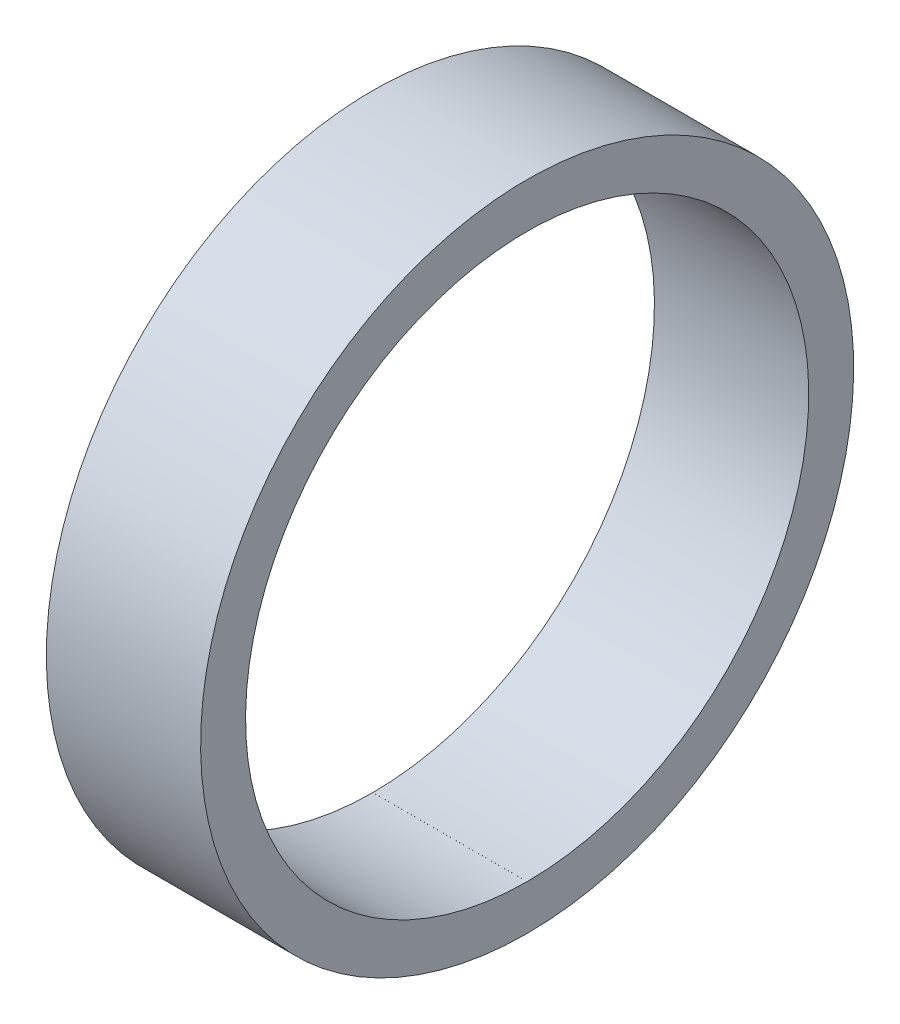
SolidWorks part; units mm, degrees
ref_plane "Front Plane" through (0, 0, 0) normal (0, 0, 1) x (1, 0, 0)
ref_plane "Top Plane" through (0, 0, 0) normal (0, 1, 0) x (1, 0, 0)
ref_plane "Right Plane" through (0, 0, 0) normal (1, 0, 0) x (0, 0, -1)
sketch "Sketch1" plane through (0, 0, 0) normal (0, 0, 1) x (1, 0, 0)
  line L0 (0, 0) -> (26.162, 0)
  line L1 (0, 47.752) -> (26.162, 47.752) construction
  dimension "D1" = 26.162
  dimension "D2" = 47.752
revolve "Revolve-Thin1" add sketch "Sketch1" angle 359.99 about L1
equation "\"FoamCore\" = \".2\""
equation "\"MDF\" = \".2\""
equation "\"GMaterial\"= \".2\""
equation "\"PVCMountDiameter\" = \"0.5in\""
equation "\"PVCMountDistanceToEdge\" = \"0.5\""
equation "\"PVCThickness\" = \"0.13in\""
equation "\"PVCDiameter\" = 1.5in"
equation "\"BaseWidth\" = \"8in\""
equation "\"BaseLength\" = \"10in\""
equation "\"BallDiameter\" = \"1.57in\""
equation "\"BaseGap\" = \"4in\""
equation "\"FunnelTopDiameter\" = \"8in\""
equation "\"FunnelTopDepth\" = \"0.5in\""
equation "\"BallGap\" = \"0.1in\""
equation "\"FunnelLength\" = 3in"
equation "\"FunnelMaterial\" = 0.1in"
equation "\"FunnelLowerDiameter\" = 1.9in"
equation "\"FunnelDepth\" = 1.5in"
equation "\"FunnelBendLength\" = 2*pi*\"FunnelLowerDiameter\"/2*135"
equation "\"AmmoFeederLength\" = 1.5in + 76mm"
equation "\"WheelThickness\" = 0.5in"
equation "\"LauncherWheelDiameter\" = 76mm"
equation "\"MotorFrontLength\" = 0.95in"
equation "\"MotorBodyTotalLength\" = 2.03in"
equation "\"MotorFrontDiameter\" = 1.5in"
equation "\"MotorLowerDriveshaftDiameter\" = 0.46in"
equation "\"MotorLowerDriveshaftThickness\" = 0.25in"
equation "\"MotorFullDriveshaftLength\" = 0.78in"
equation "\"MotorDriveshaftDiameter\" = 0.23in"
equation "\"MotorDriveshaftFlatThickness\" = 0.2in"
equation "\"MotorRearDiameter\" = 31.9mm"
equation "\"MotorDriveshaftBottomToTop\" = 31.1mm"
equation "\"MotorFlatDriveshaftLength\" = 11.7mm"
equation "\"MotorDistanceBetweenLowerandTopHoles\" = 0.5in"
equation "\"MotorMountsDistanceFromEdge\" = 0.06in"
equation "\"MotorScrewMountDiameter\" = 0.1in"
equation "\"MotorScrewMountDepth\" = 0.13in"
equation "\"HBRidgeScrewHoleDeep\" = 0.18in"
equation "\"MotorMountWidth\" = \"1.61in\""
equation "\"MotorMountLength\" = \"1.58in\""
equation "\"MotorMountToEdgeGap\" = \"3.3mm\""
equation "\"MotorMountToInsideEdgeGap\" = \"6.5mm\""
equation "\"MotorMountToMountWidthGap\" = \"25.8mm\""
equation "\"MotorMountToMountLengthGap\" = \"20.5mm\""
equation "\"MotorMountMaterialThickness\" = 1.6mm"
equation "\"MotorMountBaseScrewholeDiameter\" = 3.8mm"
equation "\"MotorMountBaseDistancebetweenHoles\" = 0.8in"
equation "\"MotorMountHeight\" = 1.85in"
equation "\"HBridgeWidth\" = 2.25in"
equation "\"HBridgeLength\" = 1.40in"
equation "\"UnoWidth\" = 3.13in"
equation "\"UnoLength\" = 3.06in"
equation "\"BatteryWidth\" = 1.15in"
equation "\"BatteryLength\" = 3.86in"
equation "\"ScrewDiameter\" = 2.7mm"
equation "\"MotorMountFaceScrewtoBase\" = 0.46in"
equation "\"MotorMountFaceDistanceBetweenScrews\" = 0.95in"
equation "\"MotorMountFaceMiddletoEdge\" = 0.16in"
equation "\"MotorMountFaceBottomtoEdge\" = 0.42in"
equation "\"MotorMountCenterholeHeight\" = 1.04in"
equation "\"MotorMountCenterholetoEdge\" = 0.25in"
equation "\"MovingWheelDiameter\" = 76mm"
equation "\"MovingWheelThickness\" = 0.5in"
equation "\"BraceLength\" = 1in"
equation "\"BraceVerticalOffset\" = 3.5in"
equation "\"BraceHorizontalOffset\" = 2.5in"
equation "\"BaseToBaseDistance\" = 7in"
equation "\"PVCOutsideDiameter\" = \"PVCDiameter\" + 2*\"PVCThickness\""
equation "\"Distancebetweenwalls\" = 6in"
equation "\"Slidewidth\" = 0.3in"
equation "\"Slidelength\" = 0.8in"
equation "\"Bottomtofloor\" = 0.53in"
equation "\"tabdistance\" = 0.2in"
equation "\"tabwidth\" = 0.3in"
equation "\"ShooterWheelDiameter\"= 1.88in"
equation "\"ShooterWheelThick\"= 1.03in"
equation "\"ShooterRubberThick\"= 0.3in"
equation "\"D2@Sketch1\"=\"ShooterWheelDiameter\""
equation "\"D3@Revolve-Thin1\"=\"ShooterRubberThick\""
